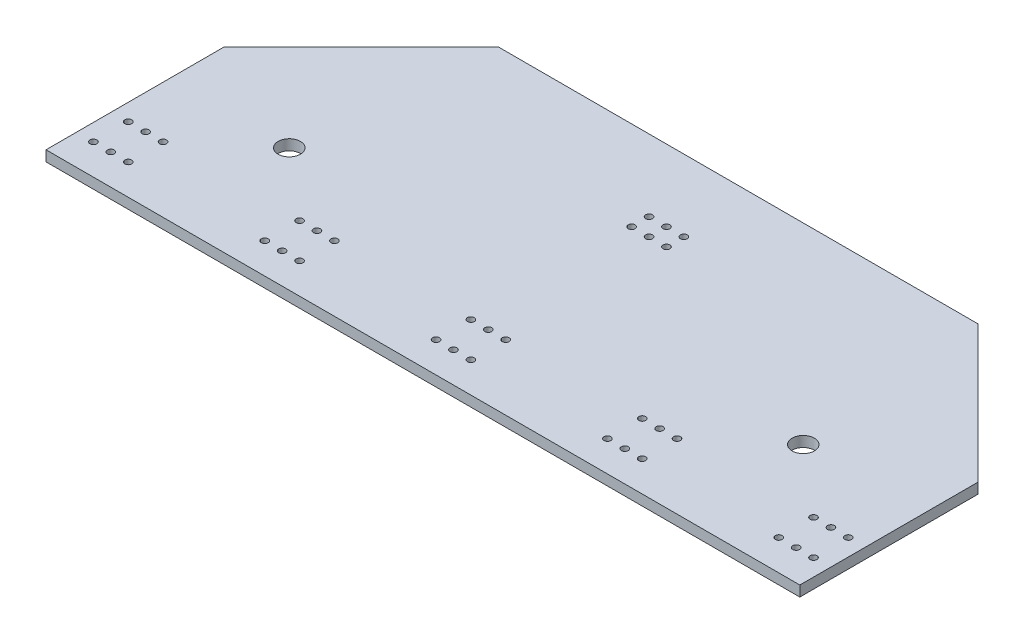
SolidWorks part; units mm, degrees
ref_plane "Front Plane" through (0, 0, 0) normal (0, 0, 1) x (1, 0, 0)
ref_plane "Top Plane" through (0, 0, 0) normal (0, 1, 0) x (1, 0, 0)
ref_plane "Right Plane" through (0, 0, 0) normal (1, 0, 0) x (0, 0, -1)
sketch "Sketch1" plane through (0, 0, 0) normal (0, 1, 0) x (1, 0, 0)
  line L0 (0, 0) -> (0, 13) construction
  line L1 (-55, -22) -> (55, -22)
  line L2 (-55, -22) -> (-55, 28)
  line L3 (-55, 28) -> (55, 28)
  line L4 (55, -22) -> (55, 28)
  line L5 (0, 0) -> (55, 28) construction
  line L6 (-55, 28) -> (0, 0) construction
  line L11 (0, 13) -> (0, 28) construction
  point P0 (0, 0)
  dimension "D1" = 110
  dimension "D2" = 28
  dimension "D6" = 22
extrude "Boss-Extrude1" add sketch "Sketch1" along normal blind 1.53
sketch "Sketch6" plane through (0, 1.53, 0) normal (0, 1, 0) x (1, 0, 0)
  line L0 (-35, 28) -> (-55, 8)
  line L1 (55, 28) -> (-55, 28) construction
  line L2 (-55, 28) -> (-55, -22) construction
  line L3 (-55, 8) -> (-55, -18)
  line L5 (-55, -22) -> (55, -22) construction
  line L6 (-52, -22) -> (-28, -22)
  line L8 (-55, -18) -> (55, -18)
  line L12 (55, -22) -> (55, 28) construction
  line L13 (55, -18) -> (55, 8)
  line L14 (55, 8) -> (35, 28)
  line L15 (35, 28) -> (-35, 28)
  line L16 (0, 0) -> (0, -18) construction
  line L17 (0, 0) -> (0, 28) construction
  line L18 (-70.5255, 34.7658) -> (-70.5255, -34.7658)
  line L23 (-70.5255, -34.7658) -> (70.5255, 34.7658) construction
  line L24 (-70.5255, 34.7658) -> (70.5255, -34.7658) construction
  line L25 (-70.5255, -34.7658) -> (70.5255, -34.7658)
  line L26 (70.5255, -34.7658) -> (70.5255, 34.7658)
  line L27 (70.5255, 34.7658) -> (-70.5255, 34.7658)
  line M37 (55, -22) -> (55, 28)
  line M38 (55, 28) -> (-55, 28)
  line M39 (-55, 28) -> (-55, -22)
  line M40 (-55, -22) -> (55, -22)
  dimension "D1" = 45
  dimension "D2" = 26
  dimension "D5" = 18
extrude "Cut-Extrude4" cut sketch "Sketch6" against normal through all contours L26 L27 L18 L25 M37 M40 M39 M38 | L8 M39 M40 M37 | L0 M38 M39 | L14 M37 M38
sketch "Sketch2" plane through (0, 1.53, 0) normal (0, 1, 0) x (1, 0, 0)
  line L0 (0, -11) -> (4.8827, -11) construction
  line L3 (-55, -18) -> (55, -18) construction
  line L24 (-2.54, -8.46) -> (0, -8.46) construction
  line L25 (0, -8.46) -> (2.54, -8.46) construction
  line L26 (0, -8.46) -> (0, -13.54) construction
  line L27 (0, -13.54) -> (2.54, -13.54) construction
  line L28 (0, -13.54) -> (-2.54, -13.54) construction
  line L29 (0, -8.46) -> (0, 0) construction
  circle A25 centre (-2.54, -8.46) radius 0.5
  circle A26 centre (0, -8.46) radius 0.5
  circle A27 centre (2.54, -8.46) radius 0.5
  circle A28 centre (-2.54, -13.54) radius 0.5
  circle A29 centre (0, -13.54) radius 0.5
  circle A30 centre (2.54, -13.54) radius 0.5
  dimension "D1" = 7
  dimension "D2" = 1
  dimension "D8" = 5.08
  dimension "D9" = 2.54
extrude "PushButtonHoles" cut sketch "Sketch2" against normal through all
sketch "Sketch7" plane through (0, 1.53, 0) normal (0, 1, 0) x (1, 0, 0)
  line L0 (-37.5, 0) -> (0, 0) construction
  line L1 (0, 0) -> (37.5, 0) construction
  line L3 (-55, 8) -> (-55, -18) construction
  line L4 (55, -18) -> (55, 8) construction
  line L5 (-55, -18) -> (55, -18) construction
  circle A0 centre (-37.5, 0) radius 1.625
  circle A1 centre (37.5, 0) radius 1.625
  dimension "D1" = 3.25
  dimension "D3" = 18
  dimension "D4" = 17.5
  dimension "D5" = 75
  dimension "D6" = 17.5
  dimension "D2" = 37.5
extrude "Mount Holes" cut sketch "Sketch7" against normal through all
sketch "Sketch5" plane through (0, 1.53, 0) normal (0, 1, 0) x (1, 0, 0)
  line L0 (-2.54, 17.54) -> (0, 17.54) construction
  line L1 (0, 17.54) -> (2.54, 17.54) construction
  line L2 (0, 17.54) -> (0, 15) construction
  line L3 (0, 15) -> (2.54, 15) construction
  line L4 (0, 15) -> (-2.54, 15) construction
  line L5 (0, 0) -> (0, 15) construction
  circle A0 centre (-2.54, 17.54) radius 0.5
  circle A1 centre (0, 17.54) radius 0.5
  circle A2 centre (2.54, 17.54) radius 0.5
  circle A3 centre (-2.54, 15) radius 0.5
  circle A4 centre (0, 15) radius 0.5
  circle A5 centre (2.54, 15) radius 0.5
  dimension "D1" = 2.54
  dimension "D2" = 2.54
  dimension "D3" = 15
extrude "RJ12Holes" cut sketch "Sketch5" against normal through all
pattern_linear "LPattern1" count 3 spacing 25 along (1, 0, 0) count 3 spacing 25 along (-1, 0, 0) of "PushButtonHoles"
